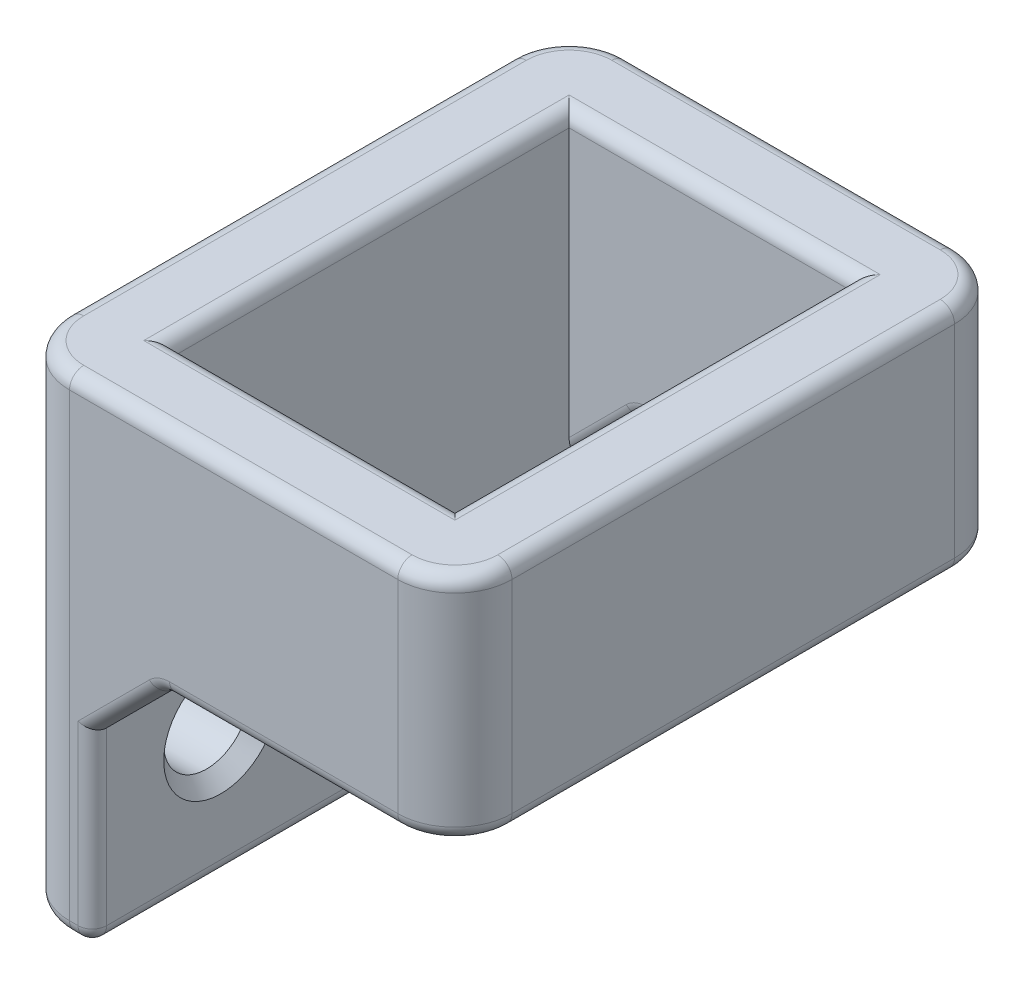
SolidWorks part; units mm, degrees
ref_plane "Plano frontal" through (0, 0, 0) normal (0, 0, 1) x (1, 0, 0)
ref_plane "Plano superior" through (0, 0, 0) normal (0, 1, 0) x (1, 0, 0)
ref_plane "Plano direito" through (0, 0, 0) normal (1, 0, 0) x (0, 0, -1)
sketch "Sketch1" plane through (0, 0, 0) normal (0, 1, 0) x (1, 0, 0)
  line L0 (-7.75, 9.75) -> (7.75, 9.75)
  line L5 (-4.75, 6.75) -> (4.75, 6.75) construction
  line L6 (-4.75, 6.75) -> (-4.75, -6.75) construction
  line L7 (-4.75, -6.75) -> (4.75, -6.75) construction
  line L8 (4.75, 6.75) -> (4.75, -6.75) construction
  line L9 (7.75, 9.75) -> (7.75, -9.75)
  line L10 (-7.75, -9.75) -> (7.75, -9.75)
  line L11 (-7.75, 9.75) -> (-7.75, -9.75)
  line L12 (-4.95, 6.95) -> (4.95, 6.95)
  line L13 (4.95, 6.95) -> (4.95, -6.95)
  line L14 (-4.95, -6.95) -> (4.95, -6.95)
  line L15 (-4.95, 6.95) -> (-4.95, -6.95)
  point P11 (0, -6.75)
  point P12 (-4.75, 0)
  dimension "D1" = 9.5
  dimension "D2" = 13.5
  dimension "D3" = 3
  dimension "D4" = 0.2
extrude "Boss-Extrude1" add sketch "Sketch1" along normal mid plane 8.1
sketch "Sketch2" plane through (-7.75, 0, 0) normal (-1, 0, 0) x (0, 0, 1)
  line L0 (9.75, 4.05) -> (9.75, -4.05) construction
  line L1 (-9.75, -4.05) -> (9.75, -4.05)
  line L2 (-9.75, -4.05) -> (-9.75, -13.05)
  line L3 (-9.75, -13.05) -> (9.75, -13.05)
  line L4 (9.75, -4.05) -> (9.75, -13.05)
  line L5 (0, -55) -> (0, 55) construction
  circle A0 centre (-5.25, -8.55) radius 1.5
  circle A2 centre (5.25, -8.55) radius 1.5
  dimension "D1" = 3
  dimension "D2" = 3
  dimension "D3" = 3
  dimension "D4" = 3
extrude "Boss-Extrude2" add sketch "Sketch2" against normal up to surface (2.8 mm away) up to face at (-4.95, 0, 0)
chamfer "Chamfer1" distance 2.5 angle 45 2 edges at (-4.95, -4.05, -8.35) (-4.95, -4.05, 8.35)
fillet "Fillet1" radius 2 4 edges at (-7.75, -4.5, 9.75) (-7.75, -4.5, -9.75) (7.75, 0, -9.75) (7.75, 0, 9.75)
fillet "Fillet2" radius 0.5 34 edges at (-7.1642, -13.05, 9.1642) (-4.95, -13.05, 0) (-7.1642, -13.05, -9.1642) (-7.75, -13.05, 0) (7.1642, -4.05, 9.1642) (7.75, -4.05, 0) (7.1642, -4.05, -9.1642) (-4.95, -9.8, 9.75) (-5.35, -13.05, 9.75) (1.65, -4.05, 9.75) (-5.35, -13.05, -9.75) (-4.95, -9.8, -9.75) (1.65, -4.05, -9.75) (7.1642, 4.05, 9.1642) (0, 4.05, 9.75) (-7.1642, 4.05, 9.1642) (-7.75, 4.05, 0) (-7.1642, 4.05, -9.1642) (0, 4.05, -9.75) (7.1642, 4.05, -9.1642) (7.75, 4.05, 0) (1.25, -4.05, -6.95) (4.95, -4.05, 0) (1.25, -4.05, 6.95) (4.95, 4.05, 0) (0, 4.05, -6.95) (-4.95, 4.05, 0) (0, 4.05, 6.95) (-3.7, -5.3, -6.95) (-3.7, -5.3, 6.95) (-2.45, -4.05, -8.35) (-2.45, -4.05, 8.35) (-3.7, -5.3, 9.75) (-3.7, -5.3, -9.75)
chamfer "Chamfer2" distance 0.5 angle 45 2 edges at (-4.95, -8.55, -6.75) (-4.95, -8.55, 3.75)
